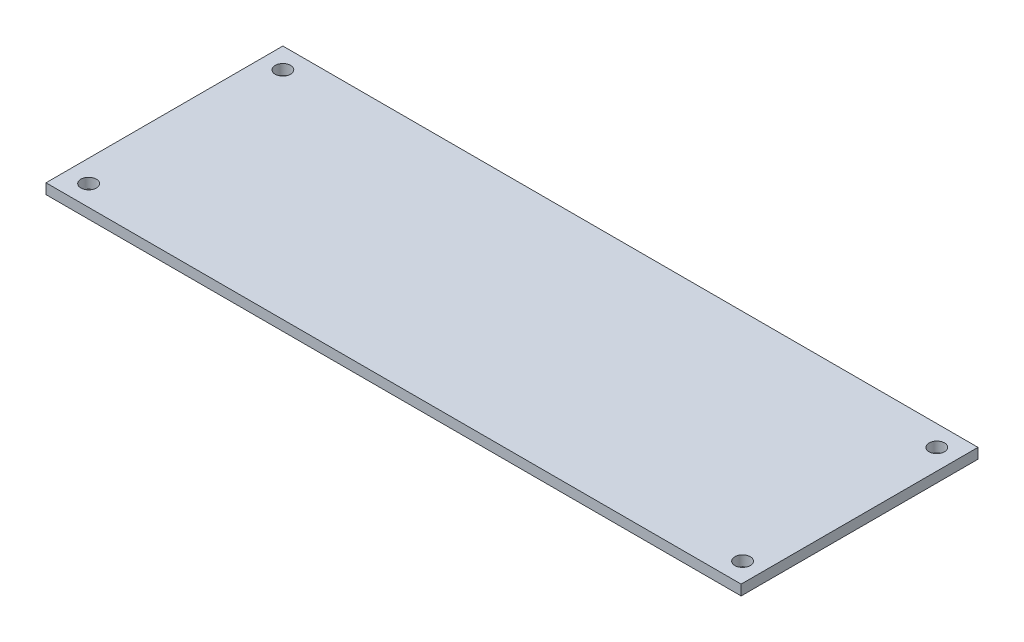
SolidWorks part; units mm, degrees
ref_plane "Front Plane" through (0, 0, 0) normal (0, 0, 1) x (1, 0, 0)
ref_plane "Top Plane" through (0, 0, 0) normal (0, 1, 0) x (1, 0, 0)
ref_plane "Right Plane" through (0, 0, 0) normal (1, 0, 0) x (0, 0, -1)
sketch "Sketch1" plane through (0, 0, 0) normal (0, 1, 0) x (1, 0, 0)
  line L0 (-63.5, 19) -> (63.5, 19) construction
  line L1 (67.5, -23) -> (-67.5, -23)
  line L2 (67.5, -23) -> (67.5, 23)
  line L3 (67.5, 23) -> (-67.5, 23)
  line L4 (-67.5, -23) -> (-67.5, 23)
  line L5 (67.5, -23) -> (-67.5, 23) construction
  line L6 (67.5, 23) -> (-67.5, -23) construction
  line L7 (0, 19) -> (0, 23) construction
  circle A0 centre (-63.5, 19) radius 1.5
  circle A1 centre (63.5, 19) radius 1.5
  circle A2 centre (63.7775, -19) radius 1.5
  circle A3 centre (-63.2225, -18.999) radius 1.5
  point P0 (0, 0)
  dimension "D1" = 3
  dimension "D4" = 127
  dimension "D5" = 3
  dimension "D6" = 3
  dimension "D7" = 3
  dimension "D8" = 38
  dimension "D9" = 127
  dimension "D10" = 4
  dimension "D11" = 38
  dimension "D2" = 135
  dimension "D3" = 46
extrude "Boss-Extrude1" add sketch "Sketch1" along normal blind 2
